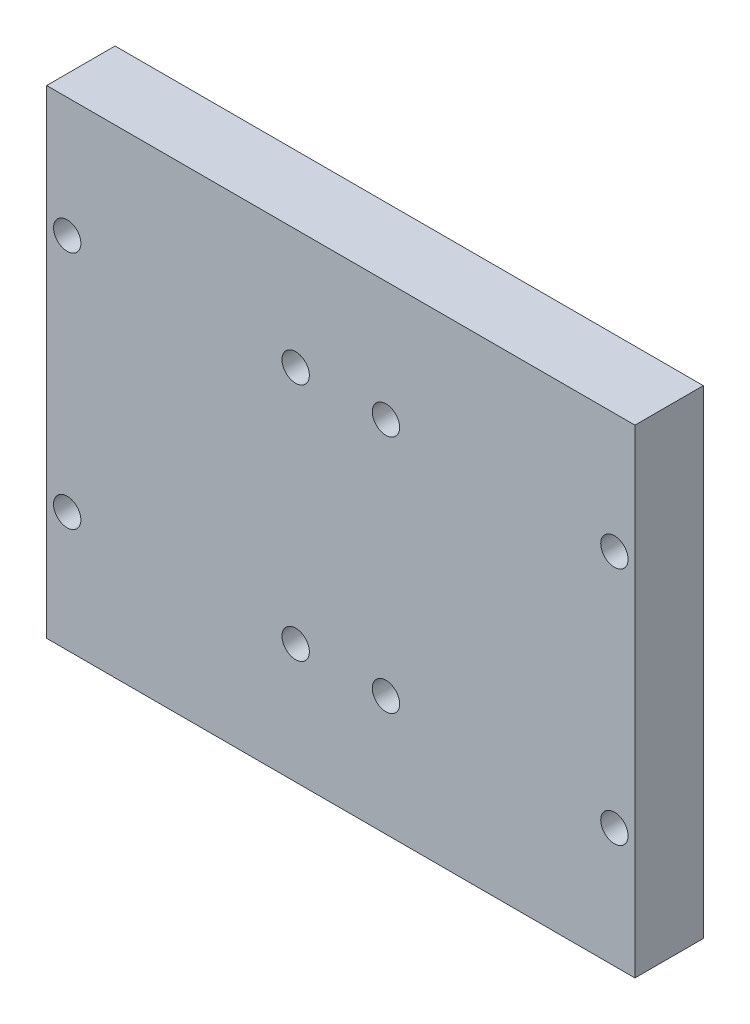
SolidWorks part; units mm, degrees
ref_plane "Plan de face" through (0, 0, 0) normal (0, 0, 1) x (1, 0, 0)
ref_plane "Plan de dessus" through (0, 0, 0) normal (0, 1, 0) x (1, 0, 0)
ref_plane "Plan de droite" through (0, 0, 0) normal (1, 0, 0) x (0, 0, -1)
sketch "Esquisse1" plane through (0, 0, 0) normal (0, 0, 1) x (1, 0, 0)
  line L0 (43, 0) -> (43, -70) construction
  line L1 (0, 0) -> (86, 0)
  line L2 (0, 0) -> (0, -70)
  line L3 (0, -70) -> (86, -70)
  line L4 (86, 0) -> (86, -70)
  circle A0 centre (3, -17.5) radius 2
  circle A1 centre (3, -52.5) radius 2
  circle A2 centre (36.4, -52.5) radius 2
  circle A3 centre (36.4, -17.5) radius 2
  circle A4 centre (49.6, -52.5) radius 2
  circle A5 centre (83, -52.5) radius 2
  circle A6 centre (83, -17.5) radius 2
  circle A7 centre (49.6, -17.5) radius 2
  dimension "D3" = 4
  dimension "D4" = 4
  dimension "D5" = 4
  dimension "D6" = 4
  dimension "D1" = 86
  dimension "D2" = 70
  dimension "D7" = 33.4
  dimension "D8" = 33.4
  dimension "D9" = 35
  dimension "D10" = 35
  dimension "D11" = 17.5
  dimension "D12" = 17.5
  dimension "D13" = 3
  dimension "D14" = 3
extrude "Boss.-Extru.1" add sketch "Esquisse1" along normal blind 10
